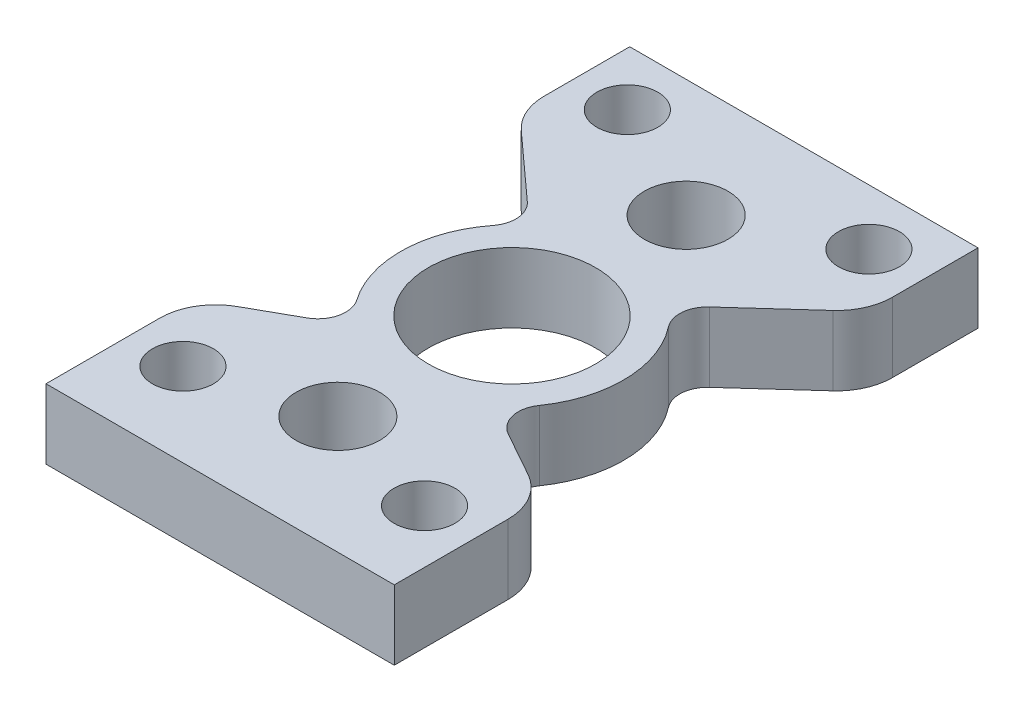
SolidWorks part; units mm, degrees
ref_plane "Front Plane" through (0, 0, 0) normal (0, 0, 1) x (1, 0, 0)
ref_plane "Top Plane" through (0, 0, 0) normal (0, 1, 0) x (1, 0, 0)
ref_plane "Right Plane" through (0, 0, 0) normal (1, 0, 0) x (0, 0, -1)
sketch "Sketch1" plane through (0, 0, 0) normal (0, 1, 0) x (1, 0, 0)
  line L0 (-15.875, -26.6065) -> (15.875, -26.6065)
  line L1 (-15.875, -26.6065) -> (-15.875, -16.2373)
  line L2 (-15.875, 26.6065) -> (15.875, 26.6065)
  line L3 (15.875, -26.6065) -> (15.875, -16.2373)
  line L4 (-15.875, 26.6065) -> (15.875, -26.6065) construction
  line L5 (15.875, 26.6065) -> (-15.875, -26.6065) construction
  line L6 (-15.875, 18.8135) -> (-15.875, 26.6065)
  line L7 (15.875, 18.8135) -> (15.875, 26.6065)
  line L8 (-14.2059, 15.0489) -> (-8.3028, 9.7005)
  line L9 (14.2059, 15.0489) -> (8.3028, 9.7005)
  line L10 (-13.2745, -11.8035) -> (-9.1619, -9.5036)
  line L11 (13.2745, -11.8035) -> (9.1619, -9.5036)
  line L12 (0, -1000) -> (0, 49000) construction
  circle A0 centre (11.0109, 21.5265) radius 2.7788
  circle A1 centre (11.0109, -18.9865) radius 2.7788
  circle A2 centre (-11.0109, -18.9865) radius 2.7788
  circle A3 centre (-11.0109, 21.5265) radius 2.7788
  arc A4 (-8.0066, 6.2546) -> (-8.3213, -5.8294) centre (0, 0) ccw
  circle A5 centre (0, 0) radius 7.62
  arc A6 (8.3213, -5.8294) -> (8.0066, 6.2546) centre (0, 0) ccw
  arc A7 (-15.875, -16.2373) -> (-13.2745, -11.8035) centre (-10.795, -16.2373) cw
  arc A8 (15.875, -16.2373) -> (13.2745, -11.8035) centre (10.795, -16.2373) ccw
  arc A9 (14.2059, 15.0489) -> (15.875, 18.8135) centre (10.795, 18.8135) ccw
  arc A10 (-14.2059, 15.0489) -> (-15.875, 18.8135) centre (-10.795, 18.8135) cw
  arc A11 (-9.1619, -9.5036) -> (-8.3213, -5.8294) centre (-10.4016, -7.2867) ccw
  arc A12 (9.1619, -9.5036) -> (8.3213, -5.8294) centre (10.4016, -7.2867) cw
  arc A13 (8.3028, 9.7005) -> (8.0066, 6.2546) centre (10.0083, 7.8182) ccw
  arc A14 (-8.3028, 9.7005) -> (-8.0066, 6.2546) centre (-10.0083, 7.8182) cw
  circle A15 centre (0, 15.875) radius 3.81
  circle A16 centre (0, -15.875) radius 3.81
  point P35 (-6.35, -7.9311)
  point P38 (6.35, -7.9311)
  point P41 (6.35, 7.9311)
  point P44 (-6.35, 7.9311)
  dimension "D6" = 5.5575
  dimension "D8" = 6.35
  dimension "D10" = 5.08
  dimension "D11" = 2.54
  dimension "D1" = 4.8641
  dimension "D2" = 5.08
  dimension "D3" = 4.8641
  dimension "D4" = 53.213
  dimension "D5" = 31.75
  dimension "D7" = 7.62
  dimension "D9" = 6.35
extrude "Boss-Extrude1" add sketch "Sketch1" along normal blind 6.35
